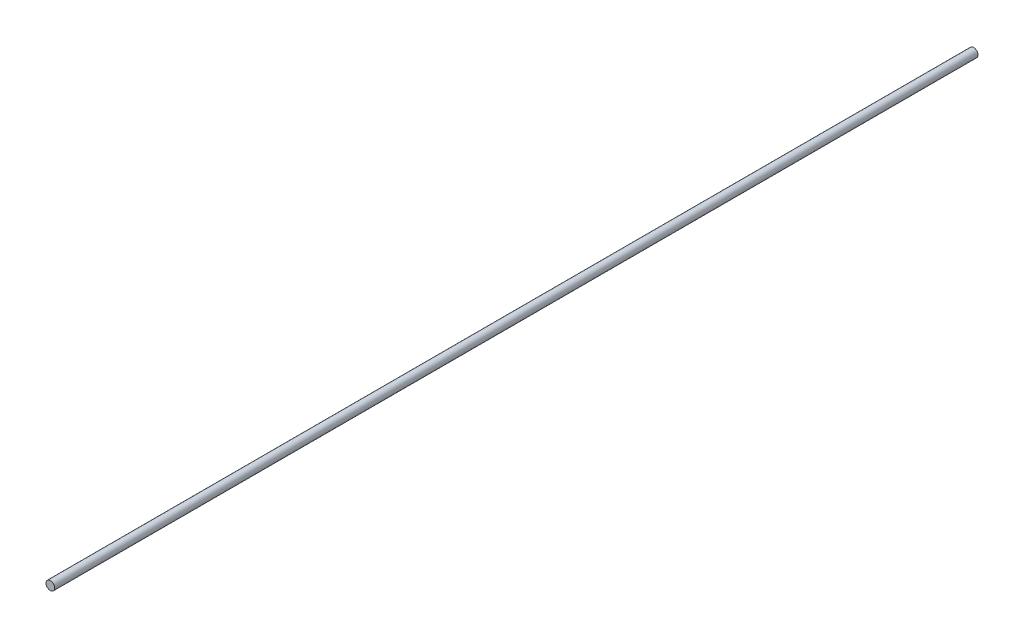
SolidWorks part; units mm, degrees
material "Zero density"
ref_plane "Piano frontale" through (0, 0, 0) normal (0, 0, 1) x (1, 0, 0)
ref_plane "Piano superiore" through (0, 0, 0) normal (0, 1, 0) x (1, 0, 0)
ref_plane "Piano destro" through (0, 0, 0) normal (1, 0, 0) x (0, 0, -1)
sketch "Schizzo1" plane through (0, 0, 0) normal (0, 0, 1) x (1, 0, 0)
  circle A0 centre (0, 0) radius 1.5
  dimension "D1" = 3
extrude "Estrusione-Estrusione1" add sketch "Schizzo1" along normal blind 320
